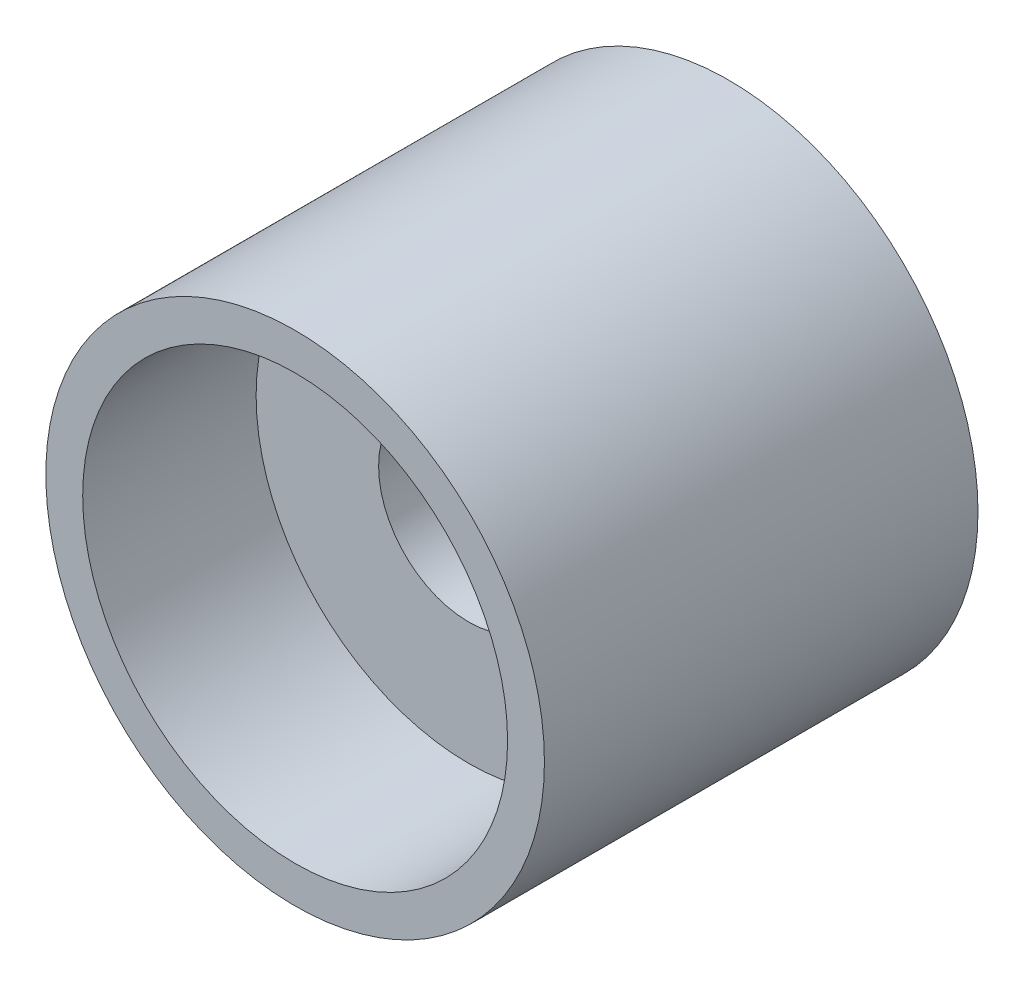
SolidWorks part; units mm, degrees
ref_plane "Front Plane" through (0, 0, 0) normal (0, 0, 1) x (1, 0, 0)
ref_plane "Top Plane" through (0, 0, 0) normal (0, 1, 0) x (1, 0, 0)
ref_plane "Right Plane" through (0, 0, 0) normal (1, 0, 0) x (0, 0, -1)
sketch "Sketch1" plane through (0, 0, 0) normal (0, 0, 1) x (1, 0, 0)
  circle A0 centre (0, 0) radius 11.5
  circle A1 centre (0, 0) radius 4.15
  dimension "D1" = 23
  dimension "D2" = 8.3
extrude "Boss-Extrude1" add sketch "Sketch1" along normal blind 20
sketch "Sketch2" plane through (0, 0, 20) normal (0, 0, 1) x (1, 0, 0)
  circle A0 centre (0, 0) radius 9.8
  circle A1 centre (0, 0) radius 11.5 construction
  dimension "D1" = 1.7
extrude "Cut-Extrude1" cut sketch "Sketch2" against normal blind 8
